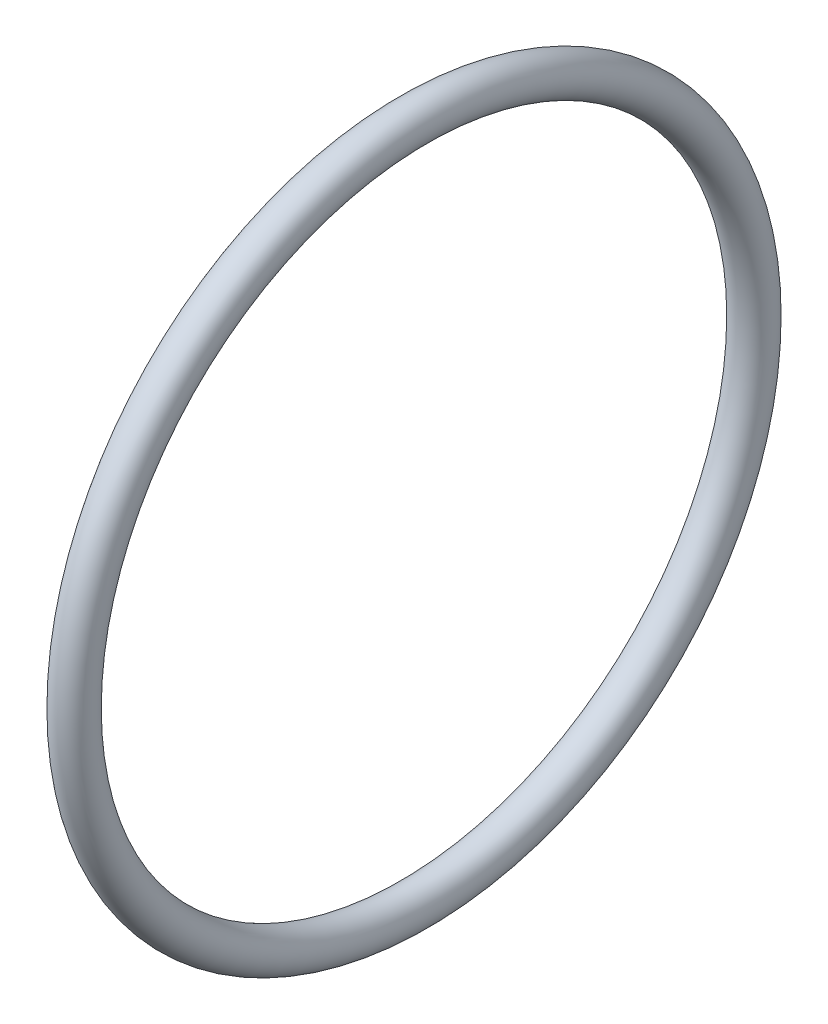
SolidWorks part; units mm, degrees
ref_plane "Front Plane" through (0, 0, 0) normal (0, 0, 1) x (1, 0, 0)
ref_plane "Top Plane" through (0, 0, 0) normal (0, 1, 0) x (1, 0, 0)
ref_plane "Right Plane" through (0, 0, 0) normal (1, 0, 0) x (0, 0, -1)
sketch "Sketch1" plane through (0, 0, 0) normal (0, 0, 1) x (1, 0, 0)
  line L0 (-15.0141, 0.7501) -> (16.7162, 0.7501) construction
  circle A0 centre (0, 27.2501) radius 1.5
  point P4 (0, 27.2501)
  dimension "D1" = 26.5
  dimension "D2" = 3
revolve "Revolve1" add sketch "Sketch1" angle 360 about L0
